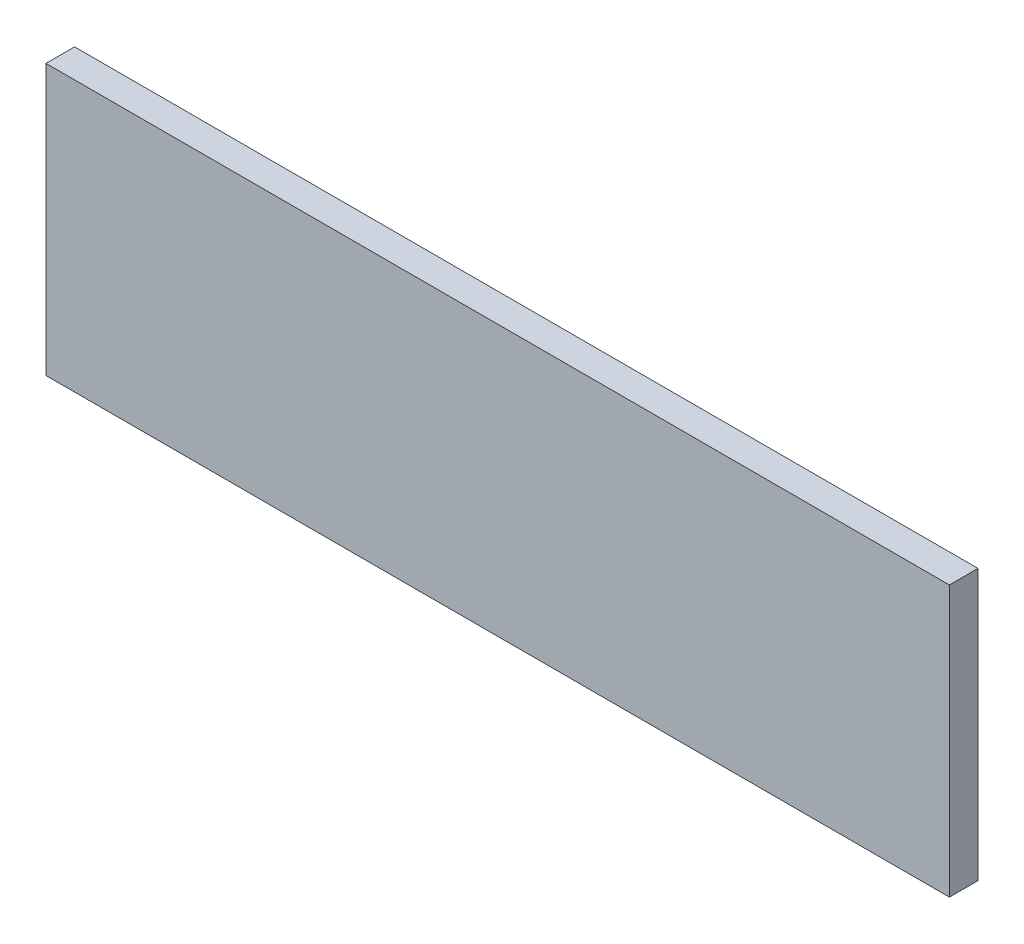
SolidWorks part; units mm, degrees
ref_plane "Front Plane" through (0, 0, 0) normal (0, 0, 1) x (1, 0, 0)
ref_plane "Top Plane" through (0, 0, 0) normal (0, 1, 0) x (1, 0, 0)
ref_plane "Right Plane" through (0, 0, 0) normal (1, 0, 0) x (0, 0, -1)
sketch "Sketch1" plane through (0, 0, 0) normal (0, 0, 1) x (1, 0, 0)
  line L1 (-50.12, 15) -> (50.12, 15)
  line L2 (-50.12, 15) -> (-50.12, -15)
  line L3 (-50.12, -15) -> (50.12, -15)
  line L4 (50.12, 15) -> (50.12, -15)
  line L5 (-50.12, 15) -> (50.12, -15) construction
  line L6 (-50.12, -15) -> (50.12, 15) construction
  point P0 (0, 0)
  dimension "D1" = 100.24
  dimension "D2" = 30
extrude "Boss-Extrude1" add sketch "Sketch1" along normal blind 3.175
